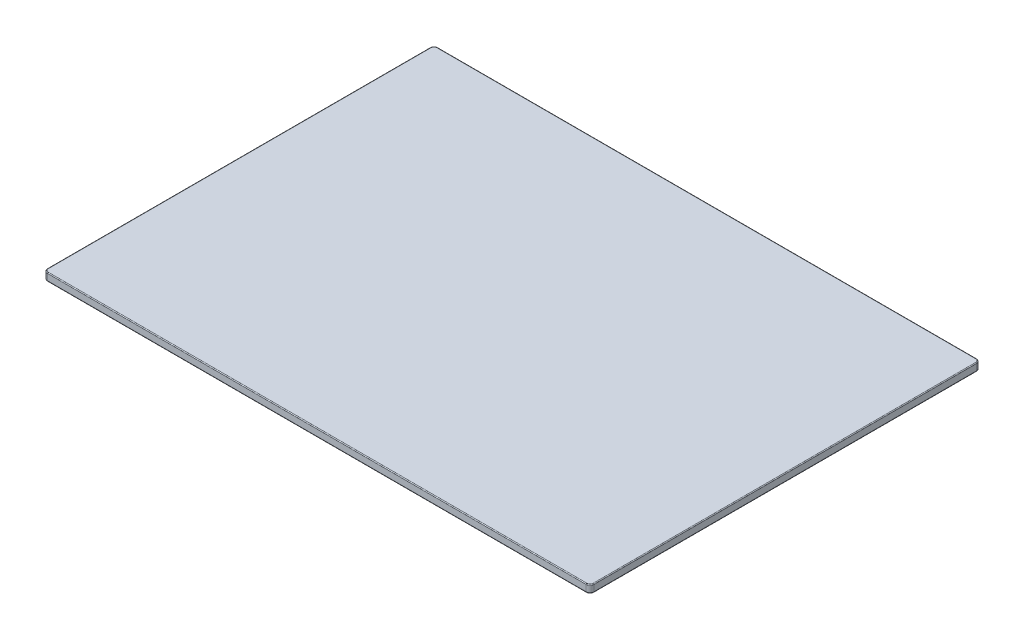
SolidWorks part; units mm, degrees
ref_plane "Front Plane" through (0, 0, 0) normal (0, 0, 1) x (1, 0, 0)
ref_plane "Top Plane" through (0, 0, 0) normal (0, 1, 0) x (1, 0, 0)
ref_plane "Right Plane" through (0, 0, 0) normal (1, 0, 0) x (0, 0, -1)
sketch "Sketch1" plane through (0, 0, 0) normal (0, 1, 0) x (1, 0, 0)
  line L1 (-350, -250) -> (350, -250)
  line L2 (-350, -250) -> (-350, 250)
  line L3 (-350, 250) -> (350, 250)
  line L4 (350, -250) -> (350, 250)
  line L5 (-350, -250) -> (350, 250) construction
  line L6 (-350, 250) -> (350, -250) construction
  point P0 (0, 0)
  dimension "D1" = 500
  dimension "D2" = 700
extrude "Boss-Extrude1" add sketch "Sketch1" along normal blind 10
fillet "Fillet2" radius 5 4 edges at (-350, 5, -250) (350, 5, -250) (350, 5, 250) (-350, 5, 250)
fillet "Fillet3" radius 1 16 edges at (-348.5355, 0, 248.5355) (0, 0, 250) (348.5355, 0, 248.5355) (350, 0, 0) (348.5355, 0, -248.5355) (0, 0, -250) (-348.5355, 0, -248.5355) (-350, 0, 0) (348.5355, 10, -248.5355) (350, 10, 0) (348.5355, 10, 248.5355) (0, 10, 250) (-348.5355, 10, 248.5355) (-350, 10, 0) (-348.5355, 10, -248.5355) (0, 10, -250)
